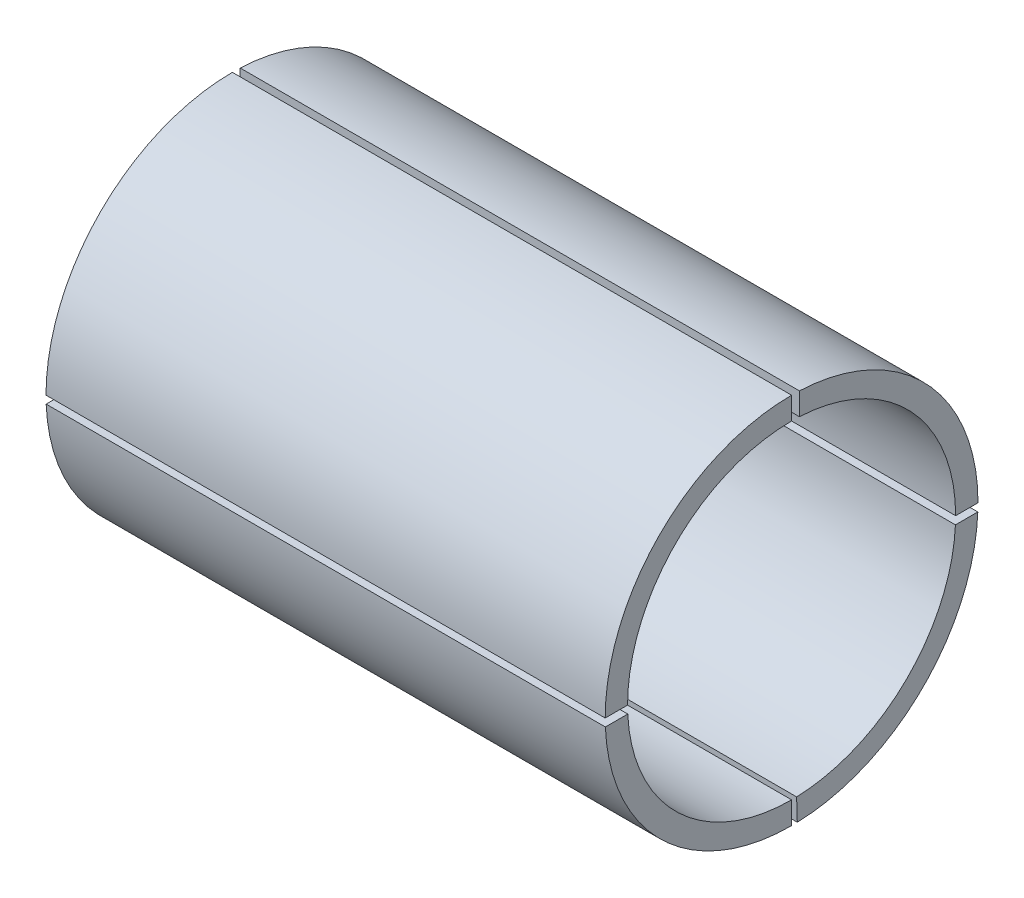
SolidWorks part; units mm, degrees
ref_plane "Front Plane" through (0, 0, 0) normal (0, 0, 1) x (1, 0, 0)
ref_plane "Top Plane" through (0, 0, 0) normal (0, 1, 0) x (1, 0, 0)
ref_plane "Right Plane" through (0, 0, 0) normal (1, 0, 0) x (0, 0, -1)
sketch "Sketch2" plane through (0, 0, 0) normal (1, 0, 0) x (0, 0, -1)
  line L0 (-5, 0) -> (-4.4, 0) construction
  line L1 (0, 5) -> (0, -5) construction
  line L2 (-4.9956, -0.2094) -> (-4.395, -0.2094) construction
  line L3 (0.2097, 4.9956) -> (0.2097, 4.395) construction
  line L4 (4.395, -0.2094) -> (4.9956, -0.2094) construction
  line L5 (0.1344, -4.3979) -> (0.1527, -4.9977) construction
  line L6 (-4.395, -0.2094) -> (-4.9956, -0.2094)
  line L7 (-4.4, 0) -> (-5, 0)
  line L8 (0, 0) -> (5, 0) construction
  line L9 (0, 5) -> (0, 4.4)
  line L10 (0.2097, 4.9956) -> (0.2097, 4.395)
  line L11 (4.4, 0) -> (5, 0)
  line L12 (4.395, -0.2094) -> (4.9956, -0.2094)
  line L13 (0, -4.4) -> (0, -5)
  line L14 (0.1344, -4.3979) -> (0.1527, -4.9977)
  arc A0 (-4.395, -0.2094) -> (0, -4.4) centre (0, 0) ccw
  arc A1 (0.1527, -4.9977) -> (4.9956, -0.2094) centre (0, 0) ccw
  arc A2 (-4.9956, -0.2094) -> (0, -5) centre (0, 0) ccw
  arc A3 (0, 5) -> (-5, 0) centre (0, 0) ccw
  arc A4 (5, 0) -> (0.2097, 4.9956) centre (0, 0) ccw
  arc A5 (0, 4.4) -> (-4.4, 0) centre (0, 0) ccw
  arc A6 (4.4, 0) -> (0.2097, 4.395) centre (0, 0) ccw
  arc A7 (0.1344, -4.3979) -> (4.395, -0.2094) centre (0, 0) ccw
  dimension "D1" = 10
  dimension "D2" = 8.8
extrude "Boss-Extrude1" add sketch "Sketch2" along normal blind 15
